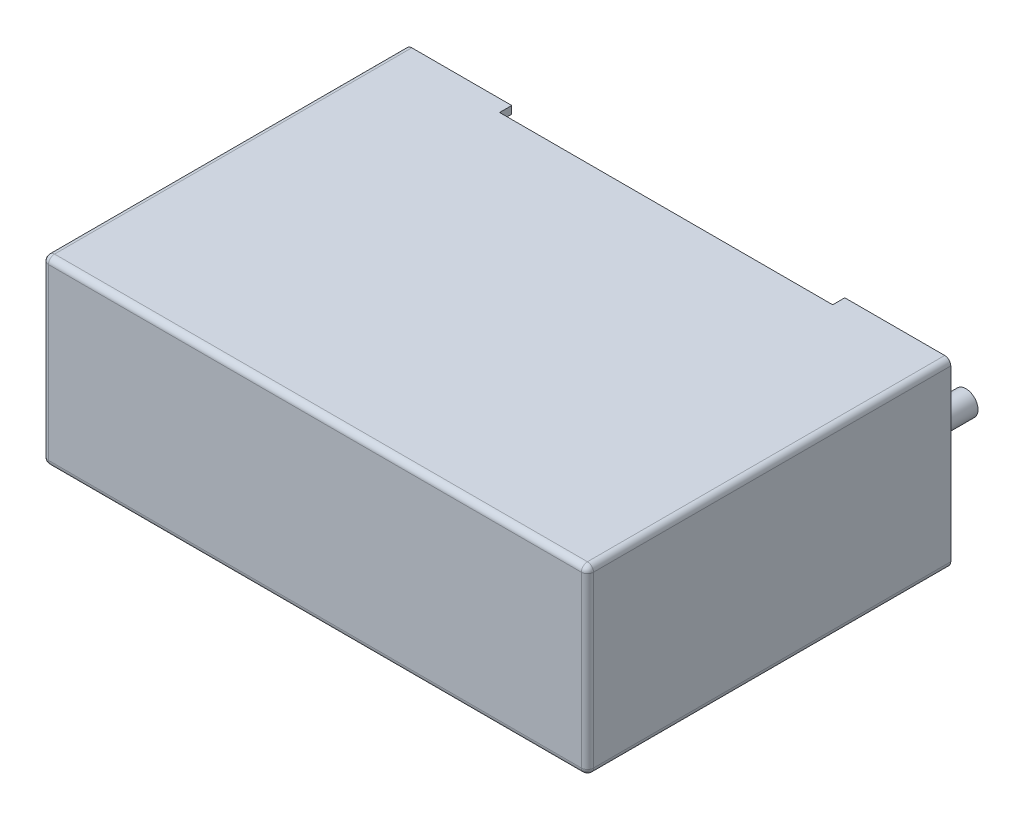
SolidWorks part; units mm, degrees
material "Duranickel(R) 301"
ref_plane "Front Plane" through (0, 0, 0) normal (0, 0, 1) x (1, 0, 0)
ref_plane "Top Plane" through (0, 0, 0) normal (0, 1, 0) x (1, 0, 0)
ref_plane "Right Plane" through (0, 0, 0) normal (1, 0, 0) x (0, 0, -1)
sketch "Sketch1" plane through (0, 0, 0) normal (0, 0, 1) x (1, 0, 0)
  line L1 (9, 3) -> (-9, 3)
  line L2 (9, 3) -> (9, -3)
  line L3 (9, -3) -> (-9, -3)
  line L4 (-9, 3) -> (-9, -3)
  line L5 (9, 3) -> (-9, -3) construction
  line L6 (9, -3) -> (-9, 3) construction
  point P0 (0, 0)
  dimension "D1" = 18
  dimension "D2" = 6
extrude "Extrude1" add sketch "Sketch1" along normal blind 12
fillet "Fillet1" radius 0.2 8 edges at (9, 3, 6) (9, -3, 6) (9, 0, 12) (0, 3, 12) (0, -3, 12) (-9, -3, 6) (-9, 3, 6) (-9, 0, 12)
sketch "Sketch3" plane through (0, -3, 0) normal (0, -1, 0) x (1, 0, 0)
  line L0 (-9, 8.5041) -> (9, 8.5041) construction
  text T0 "MKP X2 \r\n100nF \r\n275V AC" font "Century Gothic" height in points 6
  point P1 (0, 0)
  point P8 (0, 0)
  point P9 (0, 0)
  point P10 (-5.4738, 9.3365)
  point P11 (-4.6776, 9.2455)
  point P12 (-3.5526, 8.908)
extrude "Boss-Extrude1" add sketch "Sketch3" along normal blind 0.01
sketch "Sketch4" plane through (0, 0, 0) normal (0, 0, -1) x (-1, 0, 0)
  line L0 (-9, -2.8) -> (-9, 2.8) construction
  line L1 (-8.75, 2.75) -> (8.75, 2.75)
  line L2 (-8.75, 2.75) -> (-8.75, -2.75)
  line L3 (-8.75, -2.75) -> (8.75, -2.75)
  line L4 (8.75, 2.75) -> (8.75, -2.75)
  line L5 (-8.75, 2.75) -> (8.75, -2.75) construction
  line L6 (-8.75, -2.75) -> (8.75, 2.75) construction
  line L7 (-8.8, 3) -> (8.8, 3) construction
  point P0 (0, 0)
  dimension "D1" = 0.25
  dimension "D2" = 0.25
extrude "Cut-Extrude1" cut sketch "Sketch4" against normal blind 0.5
sketch "Sketch5" plane through (0, -3, 0) normal (0, -1, 0) x (1, 0, 0)
  line L0 (-8.8, 0) -> (8.8, 0) construction
  line L1 (-5.5, 0) -> (5.5, 0) construction
  line L2 (-5.5, 0) -> (-5.5, 0.4)
  line L3 (-5.5, 0.4) -> (5.5, 0.4)
  line L4 (5.5, 0) -> (5.5, 0.4)
  line L5 (-9, 0) -> (-9, 11.8) construction
  point P6 (0, 0)
  dimension "D1" = 0.4
  dimension "D2" = 3.5
extrude "Cut-Extrude5" cut sketch "Sketch5" against normal blind 6 and the other way through all
sketch "Sketch2" plane through (0, 0, 0.5) normal (0, 0, -1) x (-1, 0, 0)
  line L0 (-7.5, 0) -> (7.5, 0) construction
  circle A0 centre (-7.5, 0) radius 0.4
  circle A1 centre (7.5, 0) radius 0.4
  point P0 (0, 0)
  dimension "D1" = 0.8
  dimension "D2" = 15
extrude "Extrude2" add sketch "Sketch2" along normal blind 2.5
